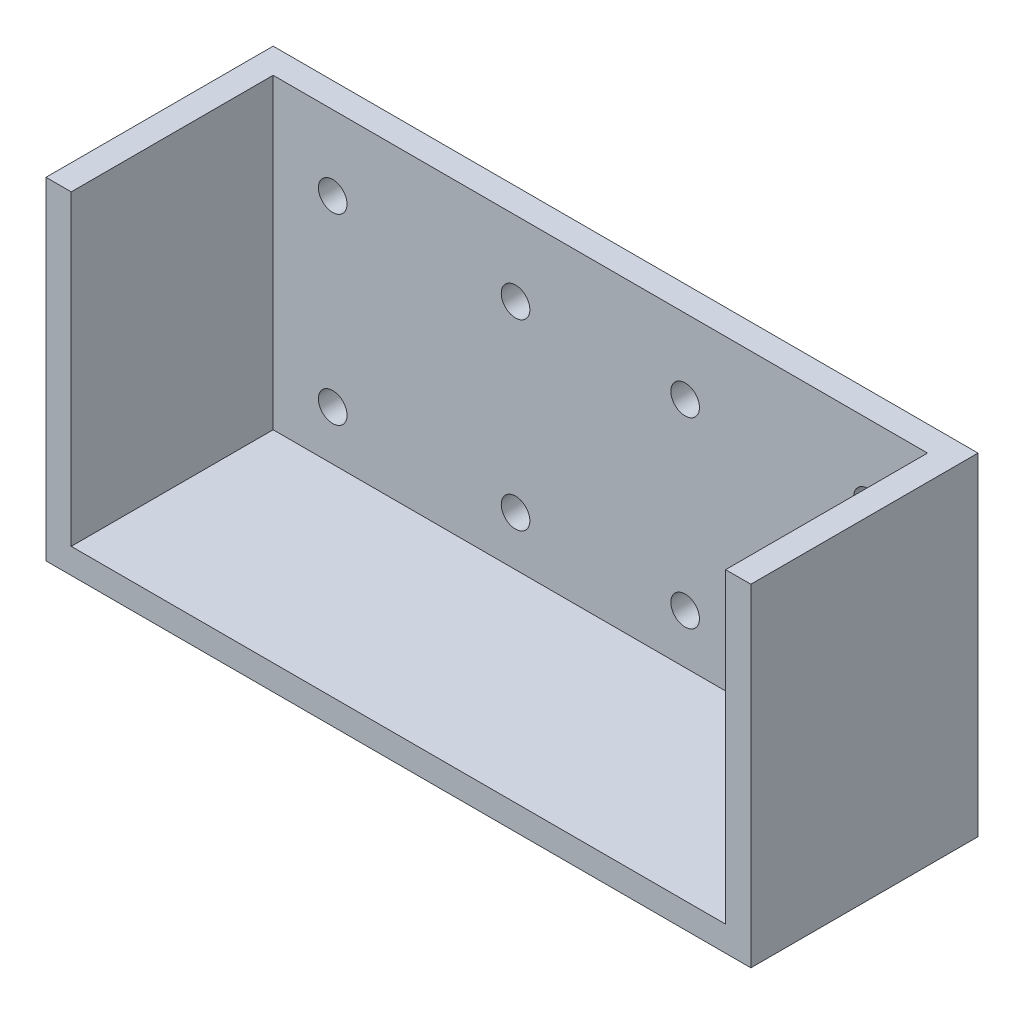
SolidWorks part; units mm, degrees
material "6061-T6 (SS)"
ref_plane "X-Y Datum" through (0, 0, 0) normal (0, 0, 1) x (1, 0, 0)
ref_plane "X-Z Datum" through (0, 0, 0) normal (0, 1, 0) x (1, 0, 0)
ref_plane "Y-Z Datum" through (0, 0, 0) normal (1, 0, 0) x (0, 0, -1)
sketch "Sketch2" plane through (0, 0, 0) normal (0, 0, 1) x (1, 0, 0)
  line L0 (-3.81, 34.8107) -> (78.5089, 34.8107)
  line L1 (0, 0) -> (74.6989, 0) construction
  line L2 (0, 0) -> (0, 31.0007) construction
  line L3 (0, 31.0007) -> (74.6989, 31.0007) construction
  line L4 (74.6989, 0) -> (74.6989, 31.0007) construction
  line L5 (78.5089, -3.81) -> (78.5089, 34.8107)
  line L6 (-3.81, -3.81) -> (78.5089, -3.81)
  line L7 (-3.81, -3.81) -> (-3.81, 34.8107)
  dimension "D1" = 74.6989
  dimension "D2" = 31.0007
  dimension "D3" = 3.81
extrude "Boss-Extrude1" add sketch "Sketch2" along normal blind 3.175
sketch "Sketch3" plane through (0, 0, 3.175) normal (0, 0, 1) x (1, 0, 0)
  line L0 (37.3494, 34.8107) -> (37.3494, 41.027) construction
  line L1 (-3.81, 34.8107) -> (-6.985, 34.8107)
  line L2 (-3.81, 34.8107) -> (-3.81, -3.81)
  line L3 (-3.81, -3.81) -> (-6.985, -3.81)
  line L4 (-6.985, 34.8107) -> (-6.985, -3.81)
  line L6 (78.5089, -3.81) -> (81.6839, -3.81)
  line L7 (81.6839, 34.8107) -> (81.6839, -3.81)
  line L8 (78.5089, 34.8107) -> (81.6839, 34.8107)
  line L9 (78.5089, 34.8107) -> (78.5089, -3.81)
  line L11 (-6.985, -3.81) -> (81.6839, -3.81)
  line L12 (-6.985, -3.81) -> (-6.985, -6.985)
  line L13 (-6.985, -6.985) -> (81.6839, -6.985)
  line L14 (81.6839, -3.81) -> (81.6839, -6.985)
  line M10 (-3.81, 34.8107) -> (-3.81, -3.81)
  line M11 (-3.81, -3.81) -> (78.5089, -3.81)
  line M12 (78.5089, -3.81) -> (78.5089, 34.8107)
  dimension "D1" = 3.175
  dimension "D2" = 3.175
extrude "Boss-Extrude2" add sketch "Sketch3" along normal blind 25.4 and the other way up to surface (3.175 mm away) contours L1 L4 L3 M10 | L13 L0 L3 L12 M11 | L8 L6 L7 M12 | L0 L13 L14 L6 L11 other way up to face at (37.3494, 15.5003, 0)
sketch "Sketch4" plane through (0, 0, 0) normal (0, 0, -1) x (-1, 0, 0)
  line L0 (-37.3494, 34.8107) -> (-37.3494, -10.1807) construction
  line L2 (-37.3494, 34.8107) -> (6.985, 34.8107) construction
  line L3 (-81.6839, 34.8107) -> (6.985, 34.8107) construction
  line L4 (-15.1822, 34.8107) -> (-15.1822, -6.985) construction
  line L5 (6.985, -6.985) -> (-81.6839, -6.985) construction
  line L6 (-26.6822, 2.4128) -> (-3.6822, 2.4128) construction
  line L7 (-26.6822, 2.4128) -> (-26.6822, 25.4128) construction
  line L8 (-26.6822, 25.4128) -> (-3.6822, 25.4128) construction
  line L9 (-3.6822, 2.4128) -> (-3.6822, 25.4128) construction
  line L10 (-26.6822, 2.4128) -> (-3.6822, 25.4128) construction
  line L11 (-26.6822, 25.4128) -> (-3.6822, 2.4128) construction
  circle A0 centre (-26.6822, 25.4128) radius 0.5619
  circle A1 centre (-3.6822, 25.4128) radius 0.5217
  circle A2 centre (-26.6822, 2.4128) radius 0.6069
  circle A3 centre (-3.6822, 2.4128) radius 0.9235
  circle A4 centre (-48.0166, 2.4128) radius 0.6069
  circle A5 centre (-71.0166, 2.4128) radius 0.9235
  circle A6 centre (-71.0166, 25.4128) radius 0.5217
  circle A7 centre (-48.0166, 25.4128) radius 0.5619
  point P11 (-15.1822, 13.9129)
extrude "Cut-Extrude1" cut sketch "Sketch4" against normal through all
hole_wizard "M3 Clearance Hole1" positions "Sketch5" profile "Sketch6" hole size "M3" standard "ANSI Metric" end condition through all
sketch "Sketch5" plane through (0, 0, 0) normal (0, 0, -1) x (-1, 0, 0)
  point P0 (-71.0166, 25.4128)
  point P3 (-71.0166, 2.4128)
  point P6 (-3.6822, 2.4128)
  point P9 (-26.6822, 2.4128)
  point P12 (-48.0166, 2.4128)
  point P15 (-48.0166, 25.4128)
  point P18 (-26.6822, 25.4128)
  point P21 (-3.6822, 25.4128)
sketch "Sketch6" plane through (71.0166, 25.4128, 0) normal (1, 0, 0) x (0, 1, 0)
  line L0 (0, 0) -> (0, 28.575)
  line L1 (0, 28.575) -> (1.8, 28.575)
  line L2 (1.8, 28.575) -> (1.8, 0)
  line L5 (1.8, 0) -> (0, 0)
  line L11 (0, -6.35) -> (0, 107.95) construction
  dimension "Thru Hole Dia." = 3.6
  dimension "Thru Hole Depth" = 28.575
